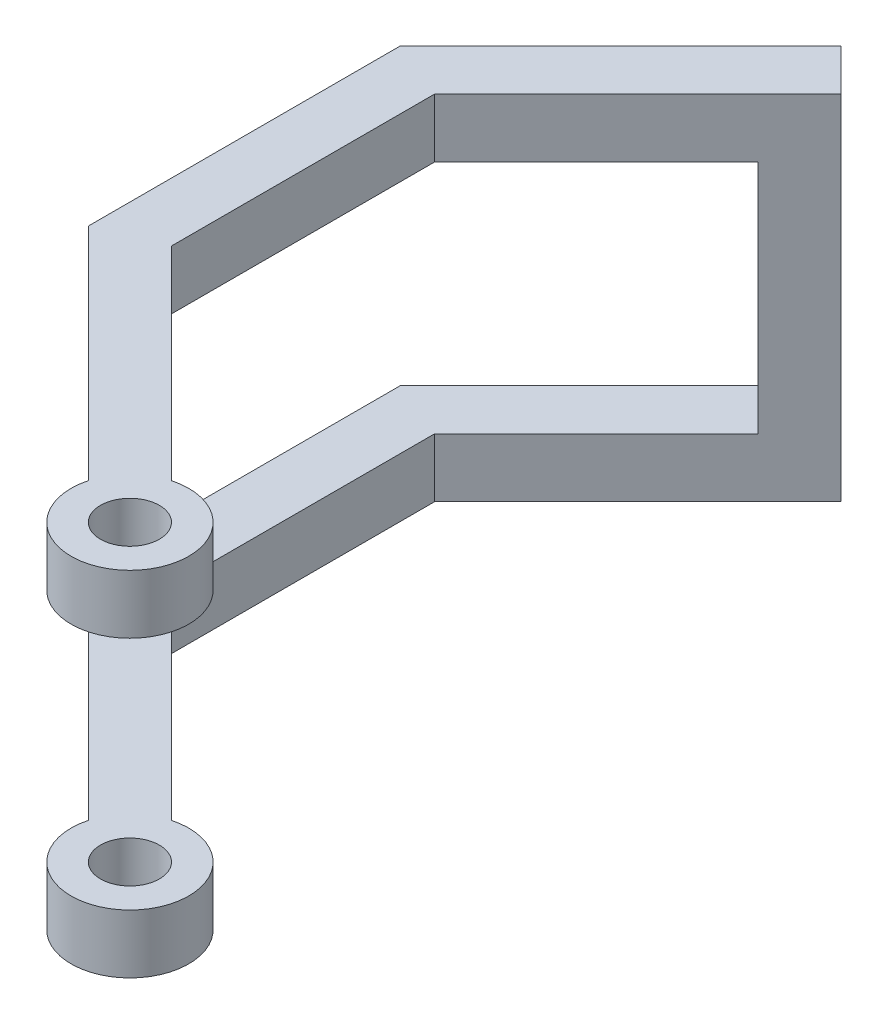
SolidWorks part; units mm, degrees
ref_plane "前视基准面" through (0, 0, 0) normal (0, 0, 1) x (1, 0, 0)
ref_plane "上视基准面" through (0, 0, 0) normal (0, 1, 0) x (1, 0, 0)
ref_plane "右视基准面" through (0, 0, 0) normal (1, 0, 0) x (0, 0, -1)
sketch "草图1" plane through (0, 0, 0) normal (0, 1, 0) x (1, 0, 0)
  line L0 (0, 0) -> (-37.4767, 37.4767)
  line L1 (-37.4767, 37.4767) -> (-37.4767, 90.4767)
  line L2 (-37.4767, 90.4767) -> (0, 127.9533)
  line L3 (0, 127.9533) -> (7.0711, 120.8823)
  line L4 (7.0711, 120.8823) -> (-27.4767, 86.3345)
  line L7 (7.0711, 7.0711) -> (-27.4767, 41.6188)
  line L8 (-27.4767, 41.6188) -> (-27.4767, 86.3345)
  arc A0 (0, 0) -> (7.0711, 7.0711) centre (9.6593, -2.5882) ccw
  circle A1 centre (9.6593, -2.5882) radius 5
extrude "凸台-拉伸1" add sketch "草图1" along normal blind 60
sketch "草图3" plane through (-37.4767, 0, 0) normal (-1, 0, 0) x (0, 0, 1)
  line L0 (-37.4767, 60) -> (-37.4767, 0) construction
  line L3 (-90.4767, 10) -> (-37.4767, 10)
  line L5 (-127.9533, 60) -> (-127.9533, 0) construction
  line L6 (-90.4767, 10) -> (-127.9533, 10)
  line L8 (-90.4767, 50) -> (-127.9533, 50)
  line L9 (-127.9533, 10) -> (-127.9533, 50)
  line L10 (12.5882, 0) -> (12.5882, 60) construction
  line L11 (-90.4767, 10) -> (12.5882, 10)
  line L13 (-90.4767, 50) -> (12.5882, 50)
  line L14 (12.5882, 10) -> (12.5882, 50)
extrude "切除-拉伸1" cut sketch "草图3" against normal blind 58
sketch "草图4" plane through (0, 10, 0) normal (0, 1, 0) x (1, 0, 0)
  line L0 (0, 127.9533) -> (7.0711, 120.8823)
  line L1 (7.0711, 120.8823) -> (0, 113.8112)
  line L2 (-27.4767, 86.3345) -> (7.0711, 120.8823) construction
  line L3 (0, 113.8112) -> (-7.0711, 120.8823)
  line L4 (0, 127.9533) -> (-37.4767, 90.4767) construction
  line L5 (-7.0711, 120.8823) -> (0, 127.9533)
extrude "凸台-拉伸2" add sketch "草图4" along normal blind 40
